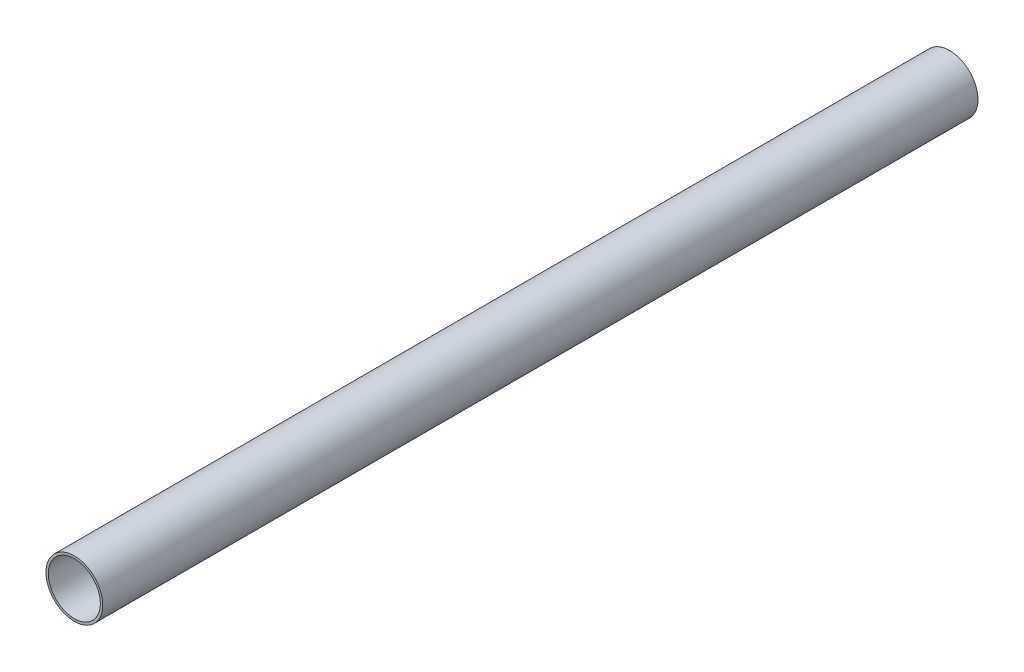
SolidWorks part; units mm, degrees
material "Karbon Fiber Boru "
ref_plane "Ön Düzlem" through (0, 0, 0) normal (0, 0, 1) x (1, 0, 0)
ref_plane "Üst Düzlem" through (0, 0, 0) normal (0, 1, 0) x (1, 0, 0)
ref_plane "Sağ Düzlem" through (0, 0, 0) normal (1, 0, 0) x (0, 0, -1)
sketch "Çizim1" plane through (0, 0, 0) normal (0, 0, 1) x (1, 0, 0)
  circle A0 centre (0, 0) radius 12
  circle A1 centre (0, 0) radius 11
  dimension "D1" = 24
  dimension "D2" = 22
extrude "Yükseklik-Ekstrüzyon1" add sketch "Çizim1" along normal blind 370
